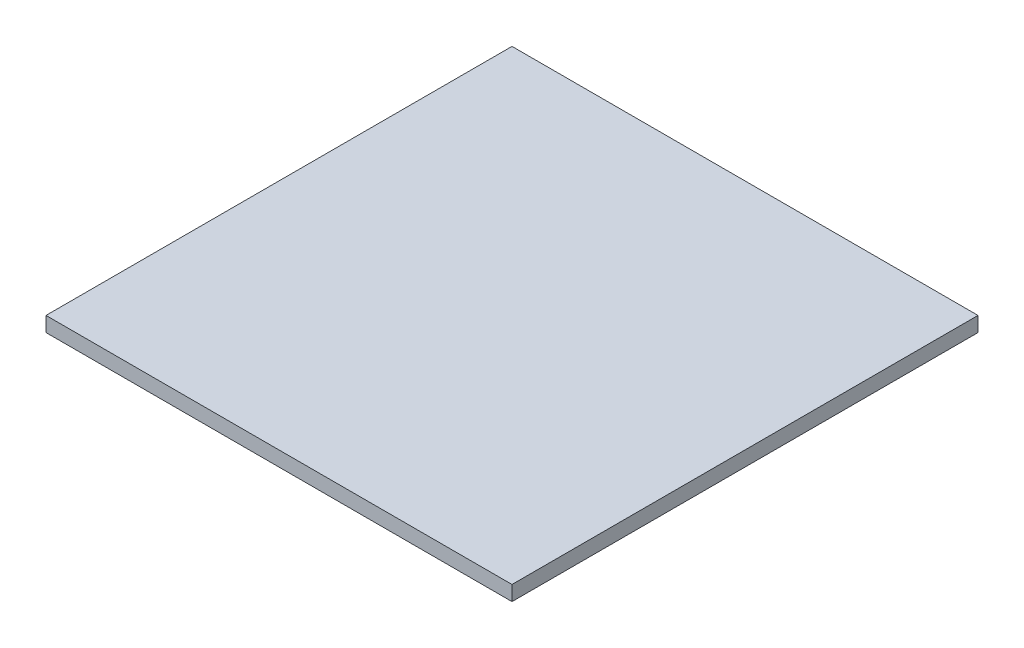
SolidWorks part; units mm, degrees
material "1060 Alloy"
ref_plane "Front Plane" through (0, 0, 0) normal (0, 0, 1) x (1, 0, 0)
ref_plane "Top Plane" through (0, 0, 0) normal (0, 1, 0) x (1, 0, 0)
ref_plane "Right Plane" through (0, 0, 0) normal (1, 0, 0) x (0, 0, -1)
sketch "Sketch1" plane through (0, 0, 0) normal (0, 1, 0) x (1, 0, 0)
  line L1 (-47, -47) -> (47, -47)
  line L2 (-47, -47) -> (-47, 47)
  line L3 (-47, 47) -> (47, 47)
  line L4 (47, -47) -> (47, 47)
  line L5 (-47, -47) -> (47, 47) construction
  line L6 (-47, 47) -> (47, -47) construction
  point P0 (0, 0)
  dimension "D1" = 94
  dimension "D2" = 94
extrude "Boss-Extrude1" add sketch "Sketch1" along normal blind 3
